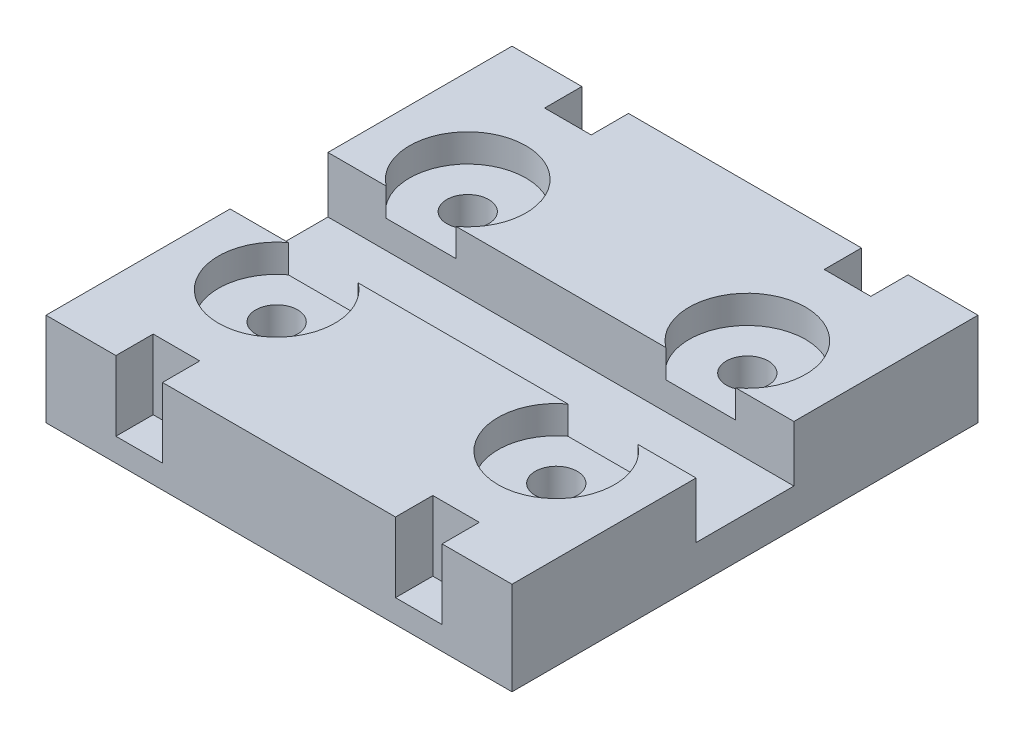
SolidWorks part; units mm, degrees
ref_plane "Front Plane" through (0, 0, 0) normal (0, 0, 1) x (1, 0, 0)
ref_plane "Top Plane" through (0, 0, 0) normal (0, 1, 0) x (1, 0, 0)
ref_plane "Right Plane" through (0, 0, 0) normal (1, 0, 0) x (0, 0, -1)
sketch "Sketch2" plane through (0, 0, 0) normal (0, 1, 0) x (1, 0, 0)
  line L1 (-87.6427, 8.4112) -> (12.3573, 8.4112)
  line L2 (-87.6427, 8.4112) -> (-87.6427, -91.5888)
  line L3 (-87.6427, -91.5888) -> (12.3573, -91.5888)
  line L4 (12.3573, 8.4112) -> (12.3573, -91.5888)
  dimension "D1" = 100
  dimension "D2" = 100
extrude "Boss-Extrude1" add sketch "Sketch2" along normal blind 20 contours L2 L1 L4 L3
sketch "Sketch3" plane through (0, 20, 0) normal (0, 1, 0) x (1, 0, 0)
  line L0 (12.3573, 8.4112) -> (12.3573, -91.5888) construction
  line L1 (12.3573, -31.5888) -> (-87.6427, -31.5888)
  line L2 (12.3573, -31.5888) -> (12.3573, -51.5888)
  line L3 (12.3573, -51.5888) -> (-87.6427, -51.5888)
  line L4 (-87.6427, -31.5888) -> (-87.6427, -51.5888)
  line L5 (-87.6427, 8.4112) -> (-87.6427, -91.5888) construction
  line L6 (-87.6427, -91.5888) -> (12.3573, -91.5888) construction
  line L7 (-87.6427, 8.4112) -> (12.3573, 8.4112) construction
  dimension "D1" = 40
  dimension "D2" = 40
sketch "Sketch4" plane through (0, 20, 0) normal (0, 1, 0) x (1, 0, 0)
extrude "Cut-Extrude1" cut sketch "Sketch3" against normal blind 12
sketch "Sketch5" plane through (0, 20, 0) normal (0, 1, 0) x (1, 0, 0)
  line L0 (12.3573, -51.5888) -> (12.3573, -91.5888) construction
  line L1 (-87.6427, -91.5888) -> (12.3573, -91.5888) construction
  circle A0 centre (-7.6427, -62.0888) radius 12.5
  dimension "D3" = 25
  dimension "D1" = 20
  dimension "D2" = 29.5
extrude "Cut-Extrude2" cut sketch "Sketch5" against normal blind 6
sketch "Sketch6" plane through (0, 20, 0) normal (0, 1, 0) x (1, 0, 0)
  line L0 (-87.6427, -51.5888) -> (-87.6427, -91.5888) construction
  line L1 (-87.6427, -91.5888) -> (12.3573, -91.5888) construction
  circle A0 centre (-67.6427, -62.0888) radius 12.5
  dimension "D3" = 25
  dimension "D1" = 20
  dimension "D2" = 29.5
extrude "Cut-Extrude3" cut sketch "Sketch6" against normal blind 6
sketch "Sketch7" plane through (0, 20, 0) normal (0, 1, 0) x (1, 0, 0)
  line L0 (-87.6427, 8.4112) -> (-87.6427, -31.5888) construction
  line L1 (-87.6427, 8.4112) -> (12.3573, 8.4112) construction
  circle A0 centre (-67.6427, -21.0888) radius 12.5
  dimension "D3" = 25
  dimension "D1" = 20
  dimension "D2" = 29.5
extrude "Cut-Extrude4" cut sketch "Sketch7" against normal blind 6
sketch "Sketch8" plane through (0, 20, 0) normal (0, 1, 0) x (1, 0, 0)
  line L0 (12.3573, 8.4112) -> (12.3573, -31.5888) construction
  line L1 (-87.6427, 8.4112) -> (12.3573, 8.4112) construction
  circle A0 centre (-7.6427, -21.0888) radius 12.5
  dimension "D3" = 25
  dimension "D1" = 20
  dimension "D2" = 29.5
extrude "Cut-Extrude5" cut sketch "Sketch8" against normal blind 6
sketch "Sketch9" plane through (0, 14, 0) normal (0, 1, 0) x (1, 0, 0)
  line L0 (-87.6427, 8.4112) -> (-87.6427, -31.5888) construction
  line L1 (-87.6427, 8.4112) -> (12.3573, 8.4112) construction
  circle A0 centre (-67.6427, -21.0888) radius 4.5
  dimension "D3" = 9
  dimension "D1" = 20
  dimension "D2" = 29.5
extrude "Cut-Extrude6" cut sketch "Sketch9" against normal blind 10
sketch "Sketch10" plane through (0, 14, 0) normal (0, 1, 0) x (1, 0, 0)
  line L0 (12.3573, 8.4112) -> (12.3573, -31.5888) construction
  line L1 (-87.6427, 8.4112) -> (12.3573, 8.4112) construction
  circle A0 centre (-7.6427, -21.0888) radius 4.5
  dimension "D3" = 9
  dimension "D1" = 20
  dimension "D2" = 29.5
extrude "Cut-Extrude7" cut sketch "Sketch10" against normal blind 10
sketch "Sketch11" plane through (0, 14, 0) normal (0, 1, 0) x (1, 0, 0)
  line L0 (12.3573, -51.5888) -> (12.3573, -91.5888) construction
  line L1 (-87.6427, -91.5888) -> (12.3573, -91.5888) construction
  circle A0 centre (-7.6427, -62.0888) radius 4.5
  dimension "D3" = 9
  dimension "D1" = 20
  dimension "D2" = 29.5
extrude "Cut-Extrude8" cut sketch "Sketch11" against normal blind 10
sketch "Sketch12" plane through (0, 14, 0) normal (0, 1, 0) x (1, 0, 0)
  line L0 (-87.6427, -51.5888) -> (-87.6427, -91.5888) construction
  line L1 (-87.6427, -91.5888) -> (12.3573, -91.5888) construction
  circle A0 centre (-67.6427, -62.0888) radius 4.5
  dimension "D3" = 9
  dimension "D1" = 20
  dimension "D2" = 29.5
extrude "Cut-Extrude9" cut sketch "Sketch12" against normal blind 10
sketch "Sketch13" plane through (0, 0, 91.5888) normal (0, 0, 1) x (1, 0, 0)
  line L0 (-87.6427, 20) -> (12.3573, 20) construction
  line L1 (-72.6427, 20) -> (-62.6427, 20)
  line L2 (-72.6427, 20) -> (-72.6427, 5)
  line L3 (-72.6427, 5) -> (-62.6427, 5)
  line L4 (-62.6427, 20) -> (-62.6427, 5)
  line L5 (-87.6427, 20) -> (-87.6427, 0) construction
  dimension "D1" = 15
  dimension "D2" = 25
  dimension "D3" = 15
extrude "Cut-Extrude11" cut sketch "Sketch13" against normal blind 8
sketch "Sketch15" plane through (0, 0, 83.5888) normal (0, 0, 1) x (1, 0, 0)
  line L0 (-72.6427, 5) -> (-62.6427, 5) construction
  line L1 (-62.6427, 5) -> (-62.6427, 20) construction
  circle A0 centre (-67.6427, 10) radius 2.5
  point P4 (-67.6427, 5)
  dimension "D1" = 5
  dimension "D2" = 5
  dimension "D3" = 5
extrude "Cut-Extrude13" cut sketch "Sketch15" against normal blind 16
sketch "Sketch16" plane through (0, 0, 0) normal (0, -1, 0) x (-1, 0, 0)
  line L0 (87.6427, 8.4112) -> (87.6427, -91.5888) construction
  line L1 (63.5927, -76.5888) -> (71.6927, -76.5888)
  line L2 (63.5927, -76.5888) -> (63.5927, -80.5888)
  line L3 (63.5927, -80.5888) -> (71.6927, -80.5888)
  line L4 (71.6927, -76.5888) -> (71.6927, -80.5888)
  line L5 (63.5927, -76.5888) -> (71.6927, -80.5888) construction
  line L6 (63.5927, -80.5888) -> (71.6927, -76.5888) construction
  line L7 (87.6427, -91.5888) -> (-12.3573, -91.5888) construction
  point P0 (67.6427, -78.5888)
  dimension "D1" = 15.95
  dimension "D2" = 15
  dimension "D3" = 4
  dimension "D4" = 8.1
extrude "Cut-Extrude14" cut sketch "Sketch16" against normal blind 14
sketch "Sketch17" plane through (0, 20, 0) normal (0, 1, 0) x (1, 0, 0)
  line L0 (-62.6427, -91.5888) -> (12.3573, -91.5888) construction
  line L1 (-12.6427, -83.5888) -> (-2.6427, -83.5888)
  line L2 (-12.6427, -83.5888) -> (-12.6427, -91.5888)
  line L3 (-12.6427, -91.5888) -> (-2.6427, -91.5888)
  line L4 (-2.6427, -83.5888) -> (-2.6427, -91.5888)
  line L5 (-12.6427, -83.5888) -> (-2.6427, -91.5888) construction
  line L6 (-12.6427, -91.5888) -> (-2.6427, -83.5888) construction
  line L7 (12.3573, -51.5888) -> (12.3573, -91.5888) construction
  point P0 (-7.6427, -87.5888)
  dimension "D1" = 0
  dimension "D2" = 15
  dimension "D3" = 8
  dimension "D4" = 10
extrude "Cut-Extrude16" cut sketch "Sketch17" against normal blind 15
sketch "Sketch19" plane through (0, 0, 83.5888) normal (0, 0, 1) x (1, 0, 0)
  line L0 (-2.6427, 5) -> (-2.6427, 20) construction
  line L1 (-2.6427, 5) -> (-12.6427, 5) construction
  circle A0 centre (-7.6427, 10) radius 2.5
  dimension "D1" = 5
  dimension "D2" = 5
  dimension "D3" = 5
extrude "Cut-Extrude17" cut sketch "Sketch19" against normal blind 16
sketch "Sketch21" plane through (0, 20, 0) normal (0, 1, 0) x (1, 0, 0)
  line L0 (-87.6427, 8.4112) -> (12.3573, 8.4112) construction
  line L1 (-62.6427, 0.4112) -> (-72.6427, 0.4112)
  line L2 (-62.6427, 0.4112) -> (-62.6427, 8.4112)
  line L3 (-62.6427, 8.4112) -> (-72.6427, 8.4112)
  line L4 (-72.6427, 0.4112) -> (-72.6427, 8.4112)
  line L5 (-62.6427, 0.4112) -> (-72.6427, 8.4112) construction
  line L6 (-62.6427, 8.4112) -> (-72.6427, 0.4112) construction
  line L7 (-87.6427, 8.4112) -> (-87.6427, -31.5888) construction
  point P0 (-67.6427, 4.4112)
  dimension "D1" = 0
  dimension "D2" = 15
  dimension "D3" = 10
  dimension "D4" = 8
extrude "Cut-Extrude19" cut sketch "Sketch21" against normal blind 15
sketch "Sketch22" plane through (0, 20, 0) normal (0, 1, 0) x (1, 0, 0)
  line L0 (-62.6427, 8.4112) -> (12.3573, 8.4112) construction
  line L1 (-2.6427, 0.4112) -> (-12.6427, 0.4112)
  line L2 (-2.6427, 0.4112) -> (-2.6427, 8.4112)
  line L3 (-2.6427, 8.4112) -> (-12.6427, 8.4112)
  line L4 (-12.6427, 0.4112) -> (-12.6427, 8.4112)
  line L5 (-2.6427, 0.4112) -> (-12.6427, 8.4112) construction
  line L6 (-2.6427, 8.4112) -> (-12.6427, 0.4112) construction
  line L7 (12.3573, 8.4112) -> (12.3573, -31.5888) construction
  point P0 (-7.6427, 4.4112)
  dimension "D1" = 0
  dimension "D2" = 15
  dimension "D3" = 10
  dimension "D4" = 8
extrude "Cut-Extrude20" cut sketch "Sketch22" against normal blind 15
sketch "Sketch23" plane through (0, 0, -0.4112) normal (0, 0, -1) x (-1, 0, 0)
  line L0 (2.6427, 5) -> (2.6427, 20) construction
  line L1 (12.6427, 5) -> (2.6427, 5) construction
  circle A0 centre (7.6427, 10) radius 2.5
  dimension "D1" = 5
  dimension "D2" = 5
  dimension "D3" = 5
extrude "Cut-Extrude21" cut sketch "Sketch23" against normal blind 16
sketch "Sketch24" plane through (0, 0, -0.4112) normal (0, 0, -1) x (-1, 0, 0)
  line L0 (62.6427, 5) -> (62.6427, 20) construction
  line L1 (72.6427, 5) -> (62.6427, 5) construction
  circle A0 centre (67.6427, 10) radius 2.5
  dimension "D1" = 5
  dimension "D2" = 5
  dimension "D3" = 5
extrude "Cut-Extrude22" cut sketch "Sketch24" against normal blind 16
sketch "Sketch25" plane through (0, 0, 0) normal (0, -1, 0) x (-1, 0, 0)
  line L0 (-12.3573, 8.4112) -> (-12.3573, -91.5888) construction
  line L1 (3.5927, -80.5888) -> (11.6927, -80.5888)
  line L2 (3.5927, -80.5888) -> (3.5927, -76.5888)
  line L3 (3.5927, -76.5888) -> (11.6927, -76.5888)
  line L4 (11.6927, -80.5888) -> (11.6927, -76.5888)
  line L5 (3.5927, -80.5888) -> (11.6927, -76.5888) construction
  line L6 (3.5927, -76.5888) -> (11.6927, -80.5888) construction
  line L8 (87.6427, -91.5888) -> (-12.3573, -91.5888) construction
  point P0 (7.6427, -78.5888)
  point P9 (3.5927, -78.5888)
  dimension "D1" = 15.95
  dimension "D2" = 15
  dimension "D3" = 8.1
  dimension "D4" = 4
extrude "Cut-Extrude23" cut sketch "Sketch25" against normal blind 15
sketch "Sketch26" plane through (0, 0, 0) normal (0, -1, 0) x (-1, 0, 0)
  line L0 (-12.3573, 8.4112) -> (-12.3573, -91.5888) construction
  line L1 (3.5927, -2.5888) -> (11.6927, -2.5888)
  line L2 (3.5927, -2.5888) -> (3.5927, -6.5888)
  line L3 (3.5927, -6.5888) -> (11.6927, -6.5888)
  line L4 (11.6927, -2.5888) -> (11.6927, -6.5888)
  line L5 (3.5927, -2.5888) -> (11.6927, -6.5888) construction
  line L6 (3.5927, -6.5888) -> (11.6927, -2.5888) construction
  line L8 (87.6427, 8.4112) -> (-12.3573, 8.4112) construction
  point P0 (7.6427, -4.5888)
  dimension "D1" = 15.95
  dimension "D2" = 15
  dimension "D3" = 4
  dimension "D4" = 8.1
extrude "Cut-Extrude24" cut sketch "Sketch26" against normal blind 15
sketch "Sketch27" plane through (0, 0, 0) normal (0, -1, 0) x (-1, 0, 0)
  line L0 (87.6427, 8.4112) -> (87.6427, -91.5888) construction
  line L1 (63.5927, -6.5888) -> (71.6927, -6.5888)
  line L2 (63.5927, -6.5888) -> (63.5927, -2.5888)
  line L3 (63.5927, -2.5888) -> (71.6927, -2.5888)
  line L4 (71.6927, -6.5888) -> (71.6927, -2.5888)
  line L5 (63.5927, -6.5888) -> (71.6927, -2.5888) construction
  line L6 (63.5927, -2.5888) -> (71.6927, -6.5888) construction
  line L8 (87.6427, 8.4112) -> (-12.3573, 8.4112) construction
  point P0 (67.6427, -4.5888)
  point P9 (67.6427, -6.5888)
  dimension "D1" = 15.95
  dimension "D2" = 15
  dimension "D3" = 8.1
  dimension "D4" = 4
extrude "Cut-Extrude25" cut sketch "Sketch27" against normal blind 15
sketch "Sketch28" plane through (0, 0, 31.5888) normal (0, 0, 1) x (1, 0, 0)
  line L1 (12.3573, 8) -> (-87.6427, 8)
  line L2 (12.3573, 8) -> (12.3573, 20)
  line L3 (12.3573, 20) -> (-87.6427, 20)
  line L4 (-87.6427, 8) -> (-87.6427, 20)
extrude "Cut-Extrude26" cut sketch "Sketch28" against normal blind 0.5
sketch "Sketch29" plane through (0, 0, 51.5888) normal (0, 0, -1) x (-1, 0, 0)
  line L1 (-12.3573, 8) -> (87.6427, 8)
  line L2 (-12.3573, 8) -> (-12.3573, 20)
  line L3 (-12.3573, 20) -> (87.6427, 20)
  line L4 (87.6427, 8) -> (87.6427, 20)
extrude "Cut-Extrude27" cut sketch "Sketch29" against normal blind 0.5
